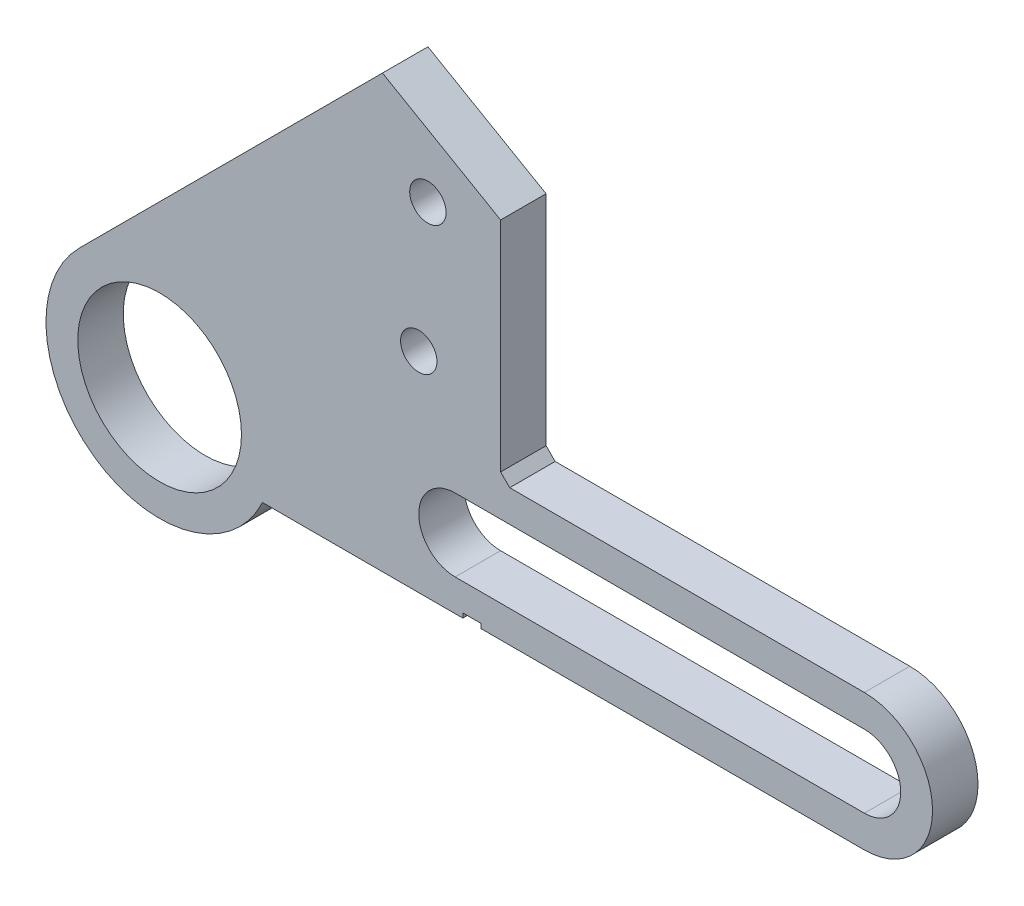
SolidWorks part; units mm, degrees
material "PBTP"
ref_plane "前视基准面" through (0, 0, 0) normal (0, 0, 1) x (1, 0, 0)
ref_plane "上视基准面" through (0, 0, 0) normal (0, 1, 0) x (1, 0, 0)
ref_plane "右视基准面" through (0, 0, 0) normal (1, 0, 0) x (0, 0, -1)
sketch "草图1" plane through (0, 0, 0) normal (0, 0, 1) x (1, 0, 0)
  line L0 (37.5, 34.6873) -> (37.5, 9.6873)
  line L7 (37.5, 34.6873) -> (24.5096, 42.1873)
  line L8 (37.5, 9.6873) -> (77.5, 9.6873)
  line L9 (11.3148, -5.3127) -> (77.5, -5.3127)
  line L10 (77.5, 6.1873) -> (32.5, 6.1873)
  line L11 (77.5, -1.8127) -> (32.5, -1.8127)
  line L12 (-8.8388, 8.8388) -> (24.5096, 42.1873)
  circle A1 centre (0, 0) radius 9
  arc A2 (-8.8388, 8.8388) -> (11.3148, -5.3127) centre (0, 0) ccw
  arc A3 (77.5, -5.3127) -> (77.5, 9.6873) centre (77.5, 2.1873) ccw
  arc A4 (77.5, -1.8127) -> (77.5, 6.1873) centre (77.5, 2.1873) ccw
  arc A6 (32.5, 6.1873) -> (32.5, -1.8127) centre (32.5, 2.1873) ccw
  point P0 (0, 0)
  dimension "D3" = 18
  dimension "D1" = 25
  dimension "D8" = 15
  dimension "D9" = 8
  dimension "D2" = 8
  dimension "D4" = 45
  dimension "D5" = 15
  dimension "D6" = 25
  dimension "D7" = 40
extrude "凸台-拉伸1" add sketch "草图1" along normal blind 5
sketch "草图2" plane through (0, 0, 0) normal (0, 0, -1) x (-1, 0, 0)
  line L0 (0, 46.9007) -> (0, -20.6571) construction
  line L1 (-31.5, 51.5598) -> (-31.5, -18.7327) construction
  line L2 (-37.5, 9.6873) -> (-37.5, 34.6873) construction
  line L3 (-77.5, 9.6873) -> (-37.5, 9.6873) construction
  circle A1 centre (-28.5, 17.6873) radius 2
  circle A2 centre (-29.5, 32.3842) radius 2
  point P13 (0, 0)
  dimension "D2" = 2
  dimension "D3" = 4
  dimension "D7" = 4
  dimension "D1" = 6
  dimension "D4" = 8
  dimension "D6" = 3
extrude "切除-拉伸1" cut sketch "草图2" against normal blind 5
chamfer "倒角1" distance 1 angle 45 1 edges at (37.5, 9.6873, 2.5)
sketch "草图3" plane through (0, 0, 0) normal (0, 0, -1) x (-1, 0, 0)
  line L0 (-11.3148, -5.3127) -> (-77.5, -5.3127) construction
  line L1 (-33.3436, -5.3127) -> (-35.3436, -5.3127)
  line L2 (-33.3436, -5.3127) -> (-33.3436, -4.8127)
  line L3 (-33.3436, -4.8127) -> (-35.3436, -4.8127)
  line L4 (-35.3436, -5.3127) -> (-35.3436, -4.8127)
  dimension "D1" = 2
  dimension "D2" = 0.5
extrude "切除-拉伸2" cut sketch "草图3" against normal blind 7
